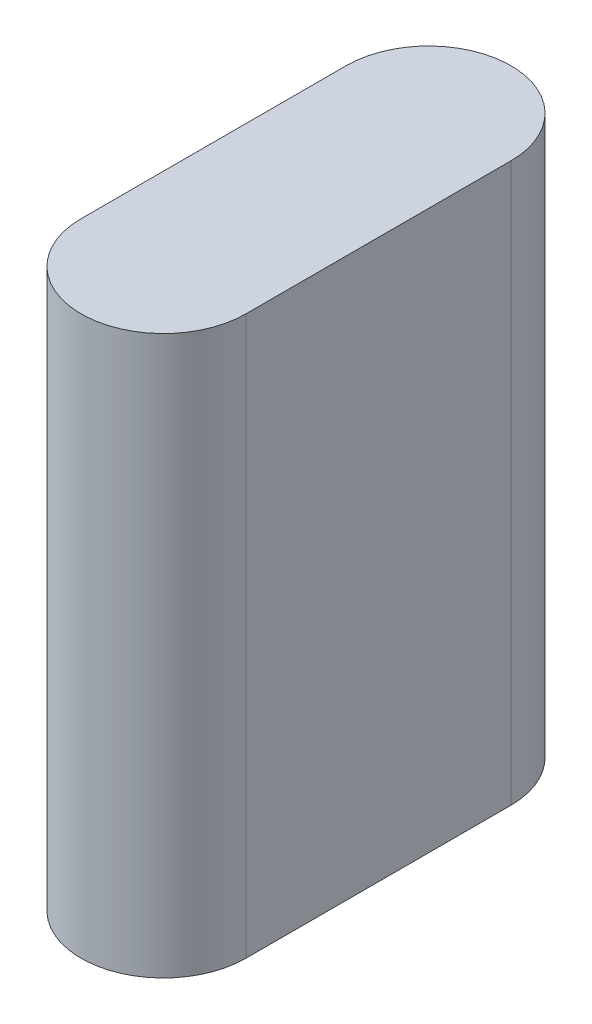
SolidWorks part; units mm, degrees
ref_plane "Front Plane" through (0, 0, 0) normal (0, 0, 1) x (1, 0, 0)
ref_plane "Top Plane" through (0, 0, 0) normal (0, 1, 0) x (1, 0, 0)
ref_plane "Right Plane" through (0, 0, 0) normal (1, 0, 0) x (0, 0, -1)
sketch "Sketch1" plane through (0, 0, 0) normal (0, 1, 0) x (1, 0, 0)
  line L0 (0, 0) -> (0, 48.26) construction
  line L1 (-15, 0) -> (-15, 48.26)
  line L2 (15, 0) -> (15, 48.26)
  arc A0 (-15, 0) -> (15, 0) centre (0, 0) ccw
  arc A1 (15, 48.26) -> (-15, 48.26) centre (0, 48.26) ccw
  point P3 (0, 24.13)
  dimension "D2" = 15
  dimension "D1" = 48.26
extrude "Boss-Extrude1" add sketch "Sketch1" along normal blind 101.6
